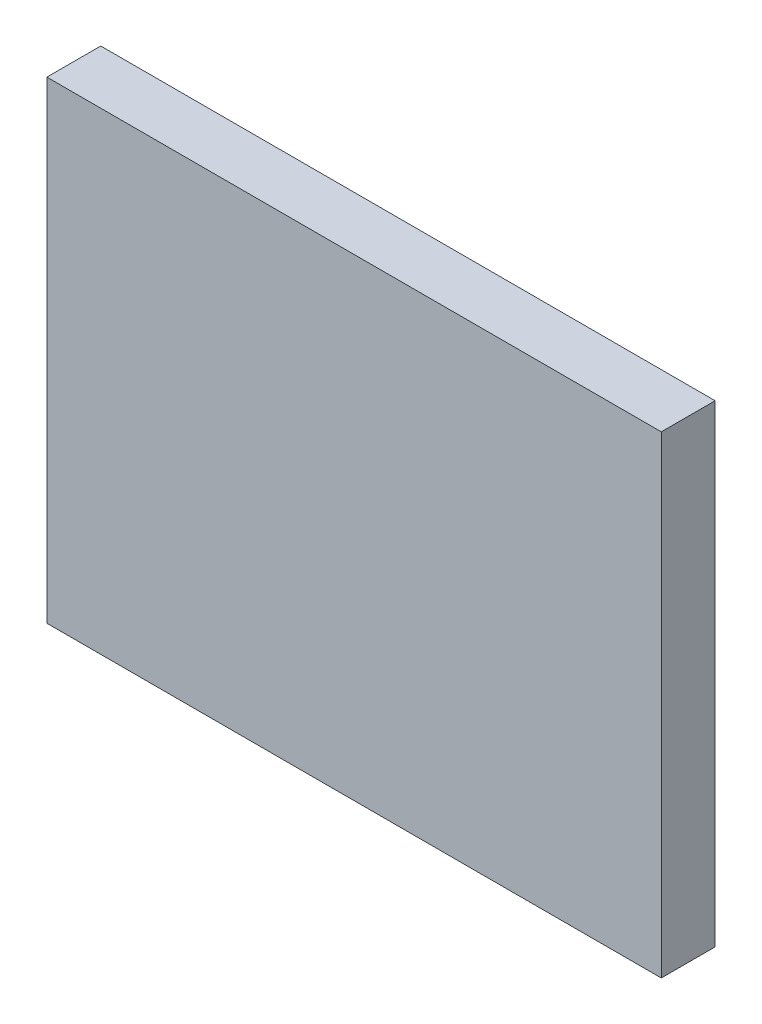
SolidWorks part; units mm, degrees
ref_plane "Ön Düzlem" through (0, 0, 0) normal (0, 0, 1) x (1, 0, 0)
ref_plane "Üst Düzlem" through (0, 0, 0) normal (0, 1, 0) x (1, 0, 0)
ref_plane "Sağ Düzlem" through (0, 0, 0) normal (1, 0, 0) x (0, 0, -1)
sketch "Çizim1" plane through (0, 0, 0) normal (0, 0, 1) x (1, 0, 0)
  line L1 (-57.0327, 43.9078) -> (57.0327, 43.9078)
  line L2 (-57.0327, 43.9078) -> (-57.0327, -43.9078)
  line L3 (-57.0327, -43.9078) -> (57.0327, -43.9078)
  line L4 (57.0327, 43.9078) -> (57.0327, -43.9078)
  line L5 (-57.0327, 43.9078) -> (57.0327, -43.9078) construction
  line L6 (-57.0327, -43.9078) -> (57.0327, 43.9078) construction
  point P0 (0, 0)
extrude "Yükseklik-Ekstrüzyon1" add sketch "Çizim1" along normal blind 10
